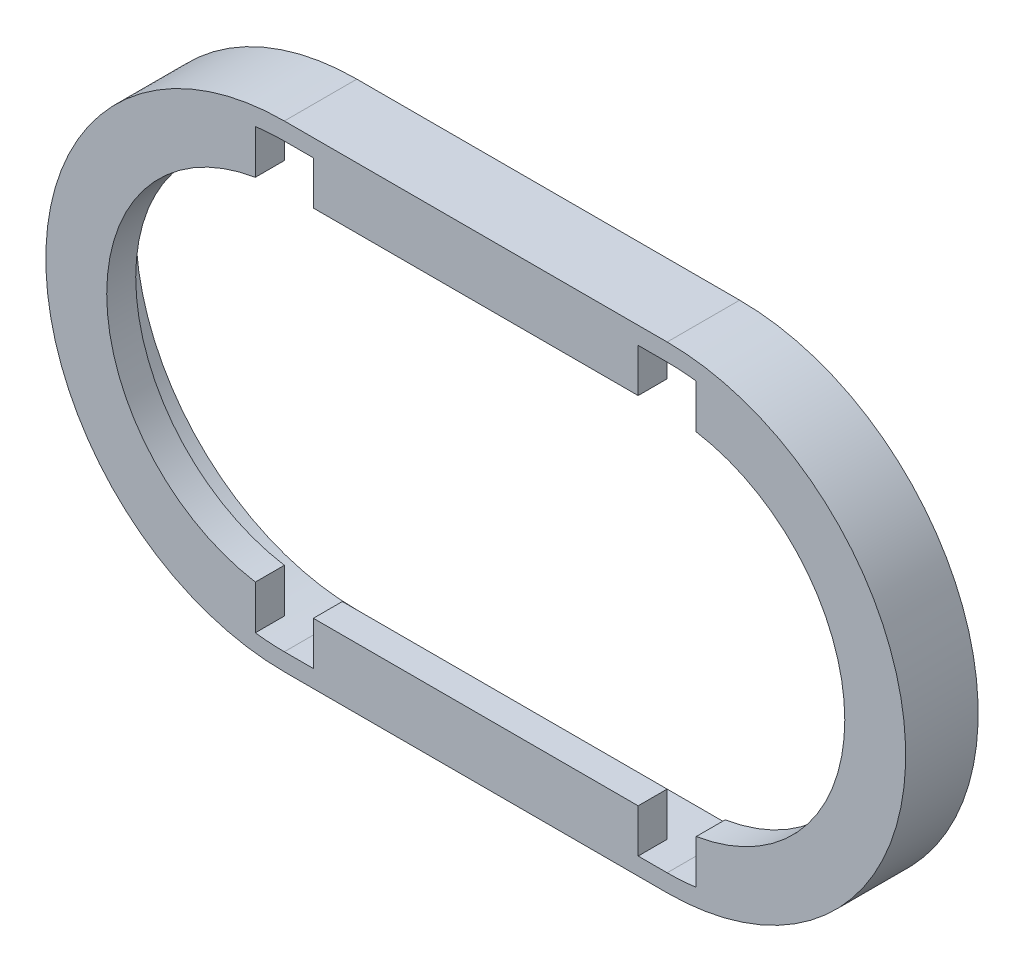
SolidWorks part; units mm, degrees
ref_plane "Front Plane" through (0, 0, 0) normal (0, 0, 1) x (1, 0, 0)
ref_plane "Top Plane" through (0, 0, 0) normal (0, 1, 0) x (1, 0, 0)
ref_plane "Right Plane" through (0, 0, 0) normal (1, 0, 0) x (0, 0, -1)
sketch "Sketch1" plane through (0, 0, 0) normal (0, 0, 1) x (1, 0, 0)
  line L0 (-34.3844, 18.7192) -> (-7.9844, 18.7192)
  line L1 (-34.3844, -11.7808) -> (-7.9844, -11.7808)
  line L2 (-34.3844, 19.9192) -> (-7.9844, 19.9192)
  line L3 (-34.3844, -12.9808) -> (-7.9844, -12.9808)
  arc A0 (-34.3844, 18.7192) -> (-34.3844, -11.7808) centre (-34.3844, 3.4692) ccw
  arc A1 (-7.9844, -11.7808) -> (-7.9844, 18.7192) centre (-7.9844, 3.4692) ccw
  arc A2 (-7.9844, -12.9808) -> (-7.9844, 19.9192) centre (-7.9844, 3.4692) ccw
  arc A3 (-34.3844, 19.9192) -> (-34.3844, -12.9808) centre (-34.3844, 3.4692) ccw
  dimension "D1" = 1.2
extrude "Boss-Extrude1" add sketch "Sketch1" against normal blind 3 and the other way blind 2
sketch "Sketch2" plane through (0, 0, 2) normal (0, 0, 1) x (1, 0, 0)
  line L0 (-34.3844, 18.7192) -> (-34.3844, -12.9808) construction
  line L1 (-7.9844, 18.7192) -> (-7.9844, -11.7808) construction
  line L2 (-9.9844, 18.7192) -> (-9.9844, -11.7808)
  line L3 (-5.9844, 18.5875) -> (-5.9844, -11.6491)
  line L4 (-36.3844, 18.5875) -> (-36.3844, -11.6491)
  line L5 (-32.3844, 18.7192) -> (-32.3844, -11.7808)
  line L6 (-34.3844, 15.7192) -> (-7.9844, 15.7192)
  line L7 (-34.3844, -8.7808) -> (-7.9844, -8.7808)
  line L8 (-7.9844, -11.7808) -> (-34.3844, -11.7808)
  line L9 (-9.9844, 18.7192) -> (-34.3844, 18.7192)
  line L10 (-5.9844, 18.7192) -> (-5.9844, -11.7808) construction
  line L11 (-36.3844, 18.7192) -> (-36.3844, -12.9808) construction
  line L12 (-32.3844, 18.7192) -> (-32.3844, -12.9808) construction
  arc A0 (-34.3844, 18.7192) -> (-34.3844, -11.7808) centre (-34.3844, 3.4692) ccw
  arc A1 (-7.9844, -11.7808) -> (-7.9844, 18.7192) centre (-7.9844, 3.4692) ccw
  arc A2 (-34.3844, 15.7192) -> (-34.3844, -8.7808) centre (-34.3844, 3.4692) ccw
  arc A3 (-7.9844, -8.7808) -> (-7.9844, 15.7192) centre (-7.9844, 3.4692) ccw
  arc A4 (-34.3844, 18.7192) -> (-34.3844, -11.7808) centre (-34.3844, 3.4692) ccw construction
  dimension "D5" = 3
  dimension "D1" = 2
  dimension "D2" = 2
  dimension "D3" = 2
  dimension "D4" = 2
extrude "Boss-Extrude2" add sketch "Sketch2" against normal blind 2
